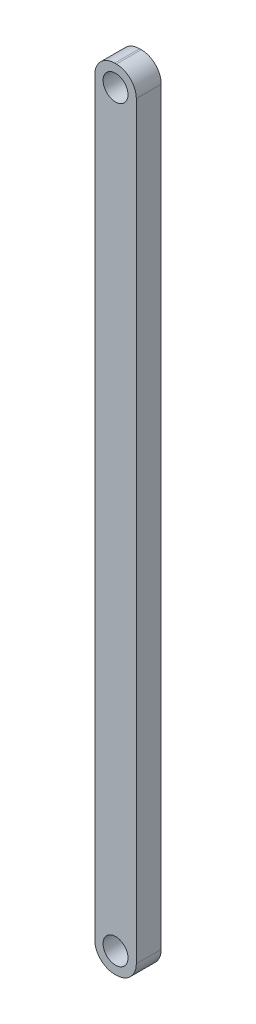
SolidWorks part; units mm, degrees
ref_plane "Front Plane" through (0, 0, 0) normal (0, 0, 1) x (1, 0, 0)
ref_plane "Top Plane" through (0, 0, 0) normal (0, 1, 0) x (1, 0, 0)
ref_plane "Right Plane" through (0, 0, 0) normal (1, 0, 0) x (0, 0, -1)
sketch "Sketch2" plane through (0, 0, 0) normal (0, 0, 1) x (1, 0, 0)
  line L1 (0, 120.65) -> (6.35, 120.65)
  line L2 (0, 120.65) -> (0, 0)
  line L3 (0, 0) -> (6.35, 0)
  line L4 (6.35, 120.65) -> (6.35, 0)
  point P4 (0, 0)
  point P6 (0, 0)
  dimension "D1" = 6.35
  dimension "D2" = 120.65
extrude "Boss-Extrude1" add sketch "Sketch2" along normal blind 3.81
fillet "Edge 1" radius 3.048 1 edges at (6.35, 120.65, 1.905)
fillet "Edge 2" radius 3.048 1 edges at (0, 120.65, 1.905)
fillet "Edge 3" radius 3.048 1 edges at (6.35, 0, 1.905)
fillet "Edge 4" radius 3.048 1 edges at (0, 0, 1.905)
sketch "Sketch4" plane through (0, 0, 3.81) normal (0, 0, 1) x (1, 0, 0)
  line L0 (6.35, 3.048) -> (6.35, 117.602) construction
  circle A0 centre (3.175, 3.175) radius 1.905
  circle A1 centre (3.175, 117.475) radius 1.905
  dimension "D1" = 3.81
  dimension "D3" = 3.81
  dimension "D2" = 3.175
  dimension "D4" = 3.175
  dimension "D5" = 114.3
extrude "Holes" cut sketch "Sketch4" against normal through all
